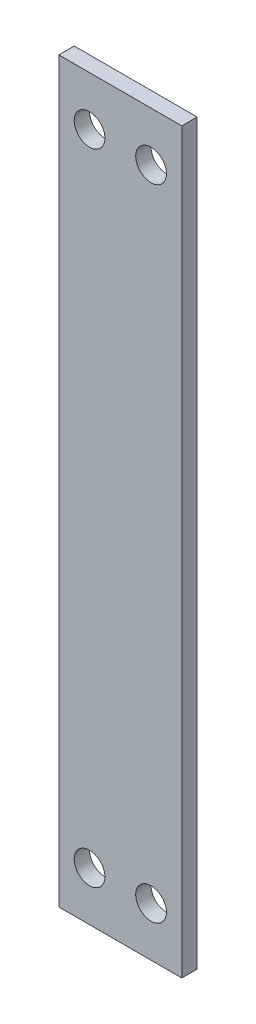
SolidWorks part; units mm, degrees
ref_plane "Front Plane" through (0, 0, 0) normal (0, 0, 1) x (1, 0, 0)
ref_plane "Top Plane" through (0, 0, 0) normal (0, 1, 0) x (1, 0, 0)
ref_plane "Right Plane" through (0, 0, 0) normal (1, 0, 0) x (0, 0, -1)
sketch "Sketch1" plane through (0, 0, 0) normal (0, 0, 1) x (1, 0, 0)
  line L0 (0, 9.9974) -> (38.1, 9.9974) construction
  line L1 (0, 0) -> (38.1, 0)
  line L2 (0, 0) -> (0, 228.6)
  line L3 (0, 228.6) -> (38.1, 228.6)
  line L4 (38.1, 0) -> (38.1, 228.6)
  line L5 (19.05, 15.24) -> (38.1, 15.24) construction
  line L6 (19.05, 225.3621) -> (38.1, 225.3621) construction
  circle A0 centre (9.525, 15.24) radius 4.7625
  circle A1 centre (28.575, 15.24) radius 4.7625
  circle A2 centre (9.525, 213.36) radius 4.7625
  circle A3 centre (28.575, 213.36) radius 4.7625
  point P13 (19.05, 9.9974)
  point P14 (28.575, 15.24)
  point P21 (19.05, 228.6)
  point P22 (28.575, 225.3621)
  point P23 (9.525, 216.7733)
  dimension "D4" = 9.525
  dimension "D6" = 9.525
  dimension "D1" = 228.6
  dimension "D2" = 38.1
  dimension "D3" = 19.05
  dimension "D5" = 15.24
  dimension "D7" = 19.05
  dimension "D8" = 15.24
extrude "Boss-Extrude1" add sketch "Sketch1" along normal blind 4.7625
